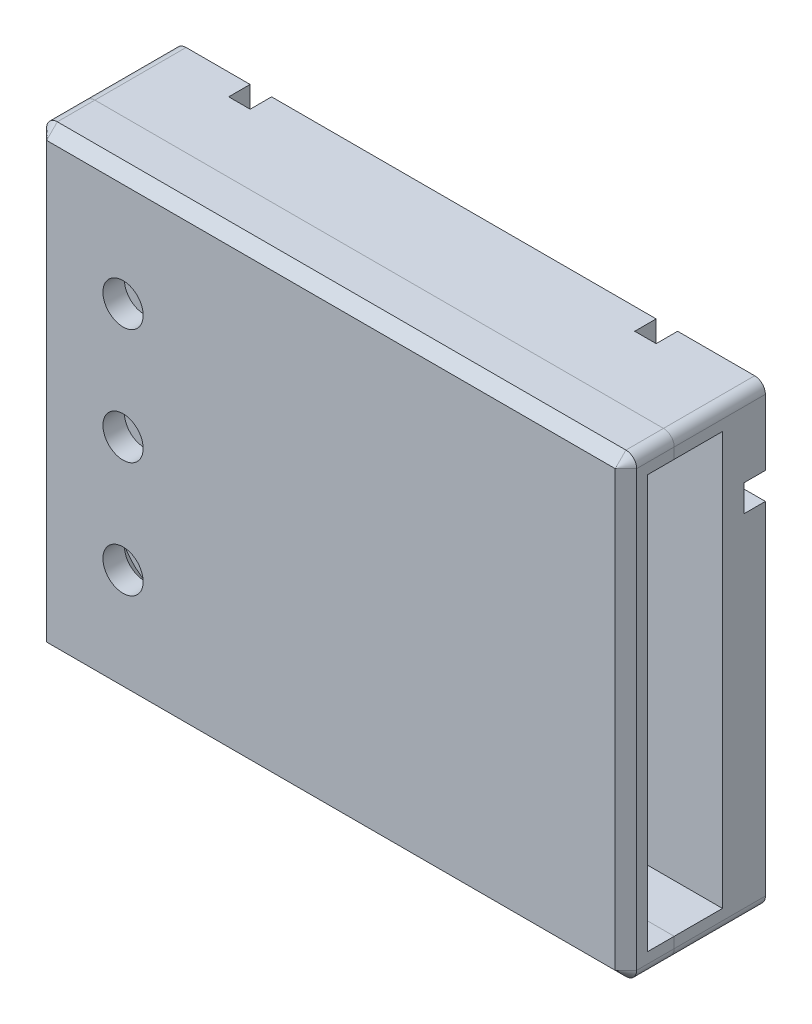
SolidWorks part; units mm, degrees
ref_plane "Ön Düzlem" through (0, 0, 0) normal (0, 0, 1) x (1, 0, 0)
ref_plane "Üst Düzlem" through (0, 0, 0) normal (0, 1, 0) x (1, 0, 0)
ref_plane "Sağ Düzlem" through (0, 0, 0) normal (1, 0, 0) x (0, 0, -1)
sketch "Sketch1" plane through (0, 0, 0) normal (0, 0, 1) x (1, 0, 0)
  line L1 (0, 0) -> (110, 0)
  line L2 (0, 0) -> (0, 85)
  line L3 (0, 85) -> (110, 85)
  line L4 (110, 0) -> (110, 85)
  dimension "D1" = 85
  dimension "D2" = 110
extrude "Boss-Extrude1" add sketch "Sketch1" along normal blind 35
shell "Shell1" thickness 4
sketch "Sketch2" plane through (0, 0, 35) normal (0, 0, 1) x (1, 0, 0)
  line L0 (110, 42.5) -> (-16.3376, 42.5) construction
  line L1 (110, 0) -> (110, 85) construction
  line L2 (55, 0) -> (55, 92.8309) construction
  line L3 (0, 0) -> (110, 0) construction
  line L4 (110, 85) -> (0, 85) construction
  line L5 (99.5, 77.5) -> (35.5, 77.5)
  line L6 (102.5, 74.5) -> (102.5, 10.5)
  line L7 (99.5, 7.5) -> (35.5, 7.5)
  line L8 (32.5, 74.5) -> (32.5, 10.5)
  line L9 (101.6213, 76.6213) -> (33.3787, 8.3787) construction
  line L10 (101.6213, 8.3787) -> (33.3787, 76.6213) construction
  line L12 (16.25, 94.2227) -> (16.25, -6.2031) construction
  line L13 (0, 85) -> (0, 0) construction
  arc A0 (35.5, 7.5) -> (32.5, 10.5) centre (35.5, 10.5) cw
  arc A1 (102.5, 10.5) -> (99.5, 7.5) centre (99.5, 10.5) cw
  arc A2 (99.5, 77.5) -> (102.5, 74.5) centre (99.5, 74.5) cw
  arc A3 (35.5, 77.5) -> (32.5, 74.5) centre (35.5, 74.5) ccw
  circle A4 centre (16.25, 63.75) radius 3.75
  circle A5 centre (16.25, 42.25) radius 3.75
  circle A6 centre (16.25, 20.75) radius 3.75
  point P9 (67.5, 42.5)
  point P31 (16.25, 63.75)
  dimension "D3" = 3
  dimension "D6" = 3
  dimension "D1" = 7.5
  dimension "D2" = 7.5
  dimension "D4" = 16.25
  dimension "D5" = 21.25
extrude "Cut-Extrude1" cut sketch "Sketch2" against normal blind 5 contours A4 | A5 | A6
sketch "Sketch3" plane through (0, 0, 4) normal (0, 0, 1) x (1, 0, 0)
  line L0 (6.25, 63.75) -> (6.25, 59.0589)
  line L1 (26.25, 63.75) -> (26.25, 20.75)
  line L2 (6.25, 46.9411) -> (6.25, 38.0589)
  line L3 (110, 42.5) -> (-16.3376, 42.5) construction
  line L4 (110, 42.5) -> (-16.3376, 42.5) construction
  line L5 (6.25, 25.9411) -> (6.25, 20.75)
  line L6 (26.25, 20.75) -> (26.25, 12.75)
  line L7 (16.25, 10.75) -> (24.25, 10.75)
  line L8 (16.25, 73.75) -> (24.25, 73.75)
  line L9 (26.25, 63.75) -> (26.25, 71.75)
  arc A0 (16.25, 73.75) -> (6.25, 63.75) centre (16.25, 63.75) ccw
  arc A2 (6.25, 20.75) -> (16.25, 10.75) centre (16.25, 20.75) ccw
  arc A3 (7.9993, 56.0282) -> (7.9993, 49.9718) centre (6.25, 53) cw
  arc A4 (7.9993, 49.9718) -> (6.25, 46.9411) centre (9.75, 46.9411) ccw
  arc A5 (7.9993, 56.0282) -> (6.25, 59.0589) centre (9.75, 59.0589) cw
  arc A6 (7.9993, 35.0282) -> (6.25, 38.0589) centre (9.75, 38.0589) cw
  arc A7 (7.9993, 28.9718) -> (7.9993, 35.0282) centre (6.25, 32) ccw
  arc A8 (7.9993, 28.9718) -> (6.25, 25.9411) centre (9.75, 25.9411) ccw
  arc A9 (26.25, 12.75) -> (24.25, 10.75) centre (24.25, 12.75) cw
  arc A10 (24.25, 73.75) -> (26.25, 71.75) centre (24.25, 71.75) cw
  point P1 (6.25, 53)
  point P14 (6.25, 49.5029)
  dimension "D1" = 10.75
  dimension "D2" = 3.5
  dimension "D3" = 2
extrude "Boss-Extrude2" add sketch "Sketch3" along normal blind 22
sketch "Sketch4" plane through (0, 0, 26) normal (0, 0, 1) x (1, 0, 0)
  line L0 (26.25, 12.75) -> (26.25, 71.75) construction
  line L1 (16.25, 71.75) -> (26.25, 71.75)
  line L2 (16.25, 71.75) -> (16.25, 55.75)
  line L3 (16.25, 55.75) -> (26.25, 55.75)
  line L4 (26.25, 71.75) -> (26.25, 55.75)
  line L5 (16.25, 50.25) -> (26.25, 50.25)
  line L6 (26.25, 50.25) -> (26.25, 34.25)
  line L7 (26.25, 12.75) -> (26.25, 71.75) construction
  line L8 (26.25, 34.25) -> (16.25, 34.25)
  line L9 (16.25, 28.75) -> (26.25, 28.75)
  line L10 (16.25, 12.75) -> (26.25, 12.75)
  line L11 (26.25, 28.75) -> (26.25, 12.75)
  arc A0 (16.25, 71.75) -> (16.25, 55.75) centre (16.25, 63.75) ccw
  arc A1 (16.25, 50.25) -> (16.25, 34.25) centre (16.25, 42.25) ccw
  arc A2 (16.25, 28.75) -> (16.25, 12.75) centre (16.25, 20.75) ccw
  line M21 (26.25, 12.75) -> (26.25, 71.75)
extrude "Cut-Extrude2" cut sketch "Sketch4" against normal blind 2 contours L2 L3 L1 M21 | L2 A0 | L5 A1 L8 M21 | L9 A2 L10 M21
sketch "Sketch5" plane through (0, 0, 24) normal (0, 0, 1) x (1, 0, 0)
  line L0 (16.25, 55.75) -> (26.25, 55.75) construction
  line L1 (26.25, 71.75) -> (24.45, 71.75)
  line L2 (26.25, 71.75) -> (26.25, 55.75)
  line L3 (26.25, 55.75) -> (24.45, 55.75)
  line L4 (24.45, 71.75) -> (24.45, 55.75)
  line L5 (26.25, 34.25) -> (16.25, 34.25) construction
  line L6 (26.25, 50.25) -> (24.45, 50.25)
  line L7 (26.25, 50.25) -> (26.25, 34.25)
  line L8 (26.25, 34.25) -> (24.45, 34.25)
  line L9 (24.45, 50.25) -> (24.45, 34.25)
  line L10 (16.25, 12.75) -> (26.25, 12.75) construction
  line L11 (26.25, 28.75) -> (24.45, 28.75)
  line L12 (26.25, 28.75) -> (26.25, 12.75)
  line L13 (26.25, 12.75) -> (24.45, 12.75)
  line L14 (24.45, 28.75) -> (24.45, 12.75)
  dimension "D1" = 1.8
extrude "Cut-Extrude3" cut sketch "Sketch5" against normal blind 2
sketch "Sketch6" plane through (0, 0, 24) normal (0, 0, 1) x (1, 0, 0)
  circle A0 centre (16.25, 63.75) radius 8
  circle A1 centre (16.25, 42.25) radius 8
  circle A2 centre (16.25, 20.75) radius 8
extrude "Cut-Extrude8" cut sketch "Sketch6" against normal blind 6 contours A2 | A1 | A0
sketch "Sketch7" plane through (0, 0, 24) normal (0, 0, 1) x (1, 0, 0)
  line L0 (24.45, 71.75) -> (24.45, 55.75) construction
  line L1 (25.54, 61.75) -> (23.36, 61.75)
  line L2 (25.54, 61.75) -> (25.54, 65.75)
  line L3 (25.54, 65.75) -> (23.36, 65.75)
  line L4 (23.36, 61.75) -> (23.36, 65.75)
  line L5 (25.54, 61.75) -> (23.36, 65.75) construction
  line L6 (25.54, 65.75) -> (23.36, 61.75) construction
  line L7 (24.45, 50.25) -> (24.45, 34.25) construction
  line L8 (25.54, 40.25) -> (23.36, 40.25)
  line L9 (25.54, 40.25) -> (25.54, 44.25)
  line L10 (25.54, 44.25) -> (23.36, 44.25)
  line L11 (23.36, 40.25) -> (23.36, 44.25)
  line L12 (25.54, 40.25) -> (23.36, 44.25) construction
  line L13 (25.54, 44.25) -> (23.36, 40.25) construction
  line L14 (24.45, 28.75) -> (24.45, 12.75) construction
  line L15 (25.765, 18.75) -> (23.135, 18.75)
  line L16 (25.765, 18.75) -> (25.765, 22.75)
  line L17 (25.765, 22.75) -> (23.135, 22.75)
  line L18 (23.135, 18.75) -> (23.135, 22.75)
  line L19 (25.765, 18.75) -> (23.135, 22.75) construction
  line L20 (25.765, 22.75) -> (23.135, 18.75) construction
  point P0 (24.45, 63.75)
  point P7 (24.45, 42.25)
  point P14 (24.45, 20.75)
  dimension "D1" = 4
  dimension "D2" = 4
  dimension "D3" = 4
extrude "Cut-Extrude9" cut sketch "Sketch7" against normal up to vertex (2 mm away)
sketch "Sketch8" plane through (0, 0, 0) normal (0, 0, -1) x (-1, 0, 0)
  line L4 (0, 0) -> (0, 85)
  line L5 (0, 85) -> (-110, 85)
  line L6 (-110, 85) -> (-110, 0)
  line L7 (-110, 0) -> (0, 0)
  line L8 (0, 0) -> (0, 85)
  line L9 (0, 85) -> (-110, 85)
  line L10 (-110, 85) -> (-110, 0)
  line L11 (-110, 0) -> (0, 0)
  dimension "D1" = 0
extrude "Cut-Extrude10" cut sketch "Sketch8" against normal blind 17
sketch "Sketch9" plane through (0, 0, 17) normal (0, 0, -1) x (-1, 0, 0)
  line L1 (0, 85) -> (-110, 85)
  line L2 (0, 85) -> (0, 0)
  line L3 (0, 0) -> (-110, 0)
  line L4 (-110, 85) -> (-110, 0)
extrude "Boss-Extrude4" add sketch "Sketch9" along normal blind 8
sketch "Sketch10" plane through (0, 0, 9) normal (0, 0, -1) x (-1, 0, 0)
  circle A0 centre (-91.6359, 68.2134) radius 4
extrude "Cut-Extrude11" cut sketch "Sketch10" against normal blind 10
sketch "Sketch11" plane through (0, 0, 9) normal (0, 0, -1) x (-1, 0, 0)
  line L1 (104.3641, 65.7134) -> (-295.6359, 65.7134)
  line L2 (104.3641, 65.7134) -> (104.3641, 70.7134)
  line L3 (104.3641, 70.7134) -> (-295.6359, 70.7134)
  line L4 (-295.6359, 65.7134) -> (-295.6359, 70.7134)
  line L5 (104.3641, 65.7134) -> (-295.6359, 70.7134) construction
  line L6 (104.3641, 70.7134) -> (-295.6359, 65.7134) construction
  circle A0 centre (-91.6359, 68.2134) radius 4 construction
  point P0 (-95.6359, 68.2134)
extrude "Cut-Extrude12" cut sketch "Sketch11" against normal blind 4
sketch "Sketch12" plane through (0, 0, 9) normal (0, 0, -1) x (-1, 0, 0)
  line L1 (-89.6359, 268.2134) -> (-93.6359, 268.2134)
  line L2 (-89.6359, 268.2134) -> (-89.6359, -131.7866)
  line L3 (-89.6359, -131.7866) -> (-93.6359, -131.7866)
  line L4 (-93.6359, 268.2134) -> (-93.6359, -131.7866)
  line L5 (-89.6359, 268.2134) -> (-93.6359, -131.7866) construction
  line L6 (-89.6359, -131.7866) -> (-93.6359, 268.2134) construction
  point P0 (-91.6359, 68.2134)
extrude "Cut-Extrude13" cut sketch "Sketch12" against normal blind 4
sketch "Sketch13" plane through (0, 0, 9) normal (0, 0, -1) x (-1, 0, 0)
  line L0 (-17.9402, 72.8946) -> (-17.9402, 85)
  line L1 (0, 70.7134) -> (-88.5134, 70.7134) construction
  line L2 (0, 85) -> (-89.6359, 85) construction
  line L3 (-13.9402, 70.7134) -> (-13.9402, 85)
  line L4 (0, 70.7134) -> (-88.5134, 70.7134) construction
  line L5 (-89.6359, 64.9952) -> (-30.9441, 17.0609)
  line L6 (-89.6359, 0) -> (-89.6359, 64.7493) construction
  line L7 (-20.3309, 8.393) -> (-20.3309, 0)
  line L8 (-89.6359, 0) -> (0, 0) construction
  line L9 (-16.3309, 0) -> (-16.3309, 9.3554)
  line L10 (-16.792, 10.6673) -> (-23.3252, 16.003)
  line L11 (-88.5134, 65.7134) -> (0, 65.7134) construction
  line L12 (-84.1918, 65.7134) -> (-88.5134, 65.7134)
  line L13 (-88.5134, 65.7134) -> (-89.6359, 65.951)
  line L14 (-89.6359, 65.951) -> (-89.6359, 64.9952)
  line L15 (-19.3522, 70.7134) -> (-17.9402, 70.7134)
  line L16 (-17.9402, 70.7134) -> (-13.9402, 70.7134)
  line L17 (-17.9402, 85) -> (-13.9402, 85)
  line L18 (-20.3309, 0) -> (-16.3309, 0)
  line L19 (-27.2039, 19.6428) -> (-19.3522, 65.7134)
  line L20 (-88.5134, 65.7134) -> (0, 65.7134) construction
  line L21 (-15.2946, 65.7134) -> (-23.6309, 16.7993)
  line L22 (-27.738, 19.607) -> (-84.1918, 65.7134)
  line L23 (-25.0673, 12.2613) -> (-20.3309, 8.393)
  line L24 (-23.5667, 16.4989) -> (-23.3252, 16.003)
  line L25 (-19.3522, 65.7134) -> (-15.2946, 65.7134)
  line L26 (-20.3309, 0) -> (-16.3309, 0)
  arc A0 (-17.9402, 72.8946) -> (-19.3522, 70.7134) centre (-20.3309, 72.8946) cw
  arc A1 (-30.9441, 17.0609) -> (-25.0673, 12.2613) centre (-27.2039, 15.6428) ccw
  arc A3 (-23.6016, 16.971) -> (-23.5667, 16.4989) centre (-22.9921, 16.7787) ccw
  arc A4 (-27.2039, 19.6428) -> (-27.738, 19.607) centre (-27.4889, 19.892) cw
  arc A5 (-16.3309, 9.3554) -> (-16.792, 10.6673) centre (-17.2174, 9.7808) ccw
  dimension "D4" = 4
  dimension "D1" = 4
  dimension "D2" = 4
  dimension "D3" = 4
extrude "Cut-Extrude14" cut sketch "Sketch13" against normal blind 4 contours L9 A5 L10 L24 A3 L21 L25 L19 A4 L22 L12 L13 L14 L5 A1 L23 L7 L18 | L3 L17 L0 A0 L15 L16
sketch "Sketch14" plane through (0, 0, 13) normal (0, 0, -1) x (-1, 0, 0)
  circle A0 centre (-27.2039, 15.6428) radius 4
extrude "Cut-Extrude15" cut sketch "Sketch14" against normal blind 4
sketch "Sketch15" plane through (0, 0, 17) normal (0, 0, -1) x (-1, 0, 0)
  line L1 (-26.25, 19.5274) -> (-26.25, 12.75)
  line L2 (-26.25, 19.5274) -> (-26.25, 12.75)
  arc A2 (-26.25, 12.75) -> (-26.0215, 11.8216) centre (-24.25, 12.75) ccw
  arc A3 (-26.0215, 11.8216) -> (-26.25, 19.5274) centre (-27.2039, 15.6428) ccw
  arc A4 (-26.25, 12.75) -> (-26.0215, 11.8216) centre (-24.25, 12.75) ccw
  arc A5 (-26.0215, 11.8216) -> (-26.25, 19.5274) centre (-27.2039, 15.6428) ccw
  dimension "D1" = 0
extrude "Boss-Extrude5" add sketch "Sketch15" along normal blind 4
fillet "Fillet1" radius 2 4 edges at (0, 85, 22) (0, 0, 22) (110, 0, 22) (110, 85, 22)
chamfer "Chamfer1" distance 2 angle 45 8 edges at (110, 42.5, 35) (55, 85, 35) (0.5858, 84.4142, 35) (109.4142, 84.4142, 35) (0, 42.5, 35) (0.5858, 0.5858, 35) (109.4142, 0.5858, 35) (55, 0, 35)
ref_plane "Plane1" through (0, 0, 26) normal (0, 0, 1) x (1, 0, 0)
split "Split1" trim tools "Plane1" bodies to split 117 resulting bodies 120 121
